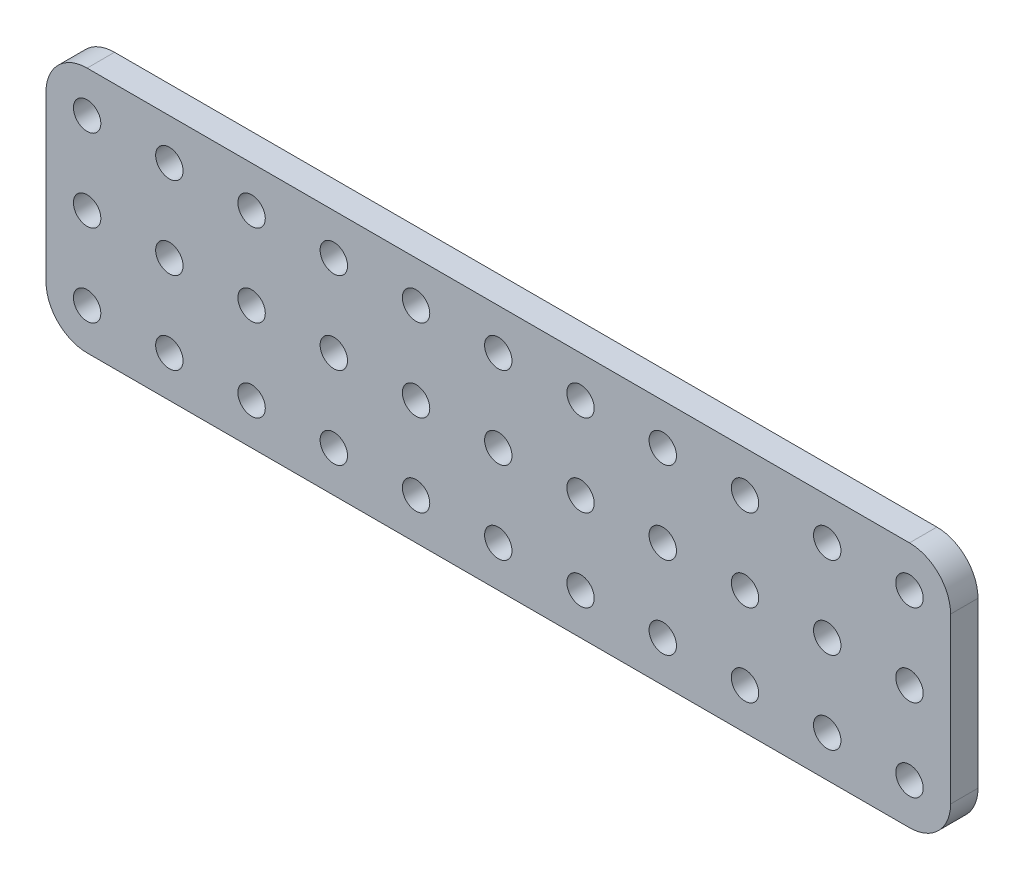
SolidWorks part; units mm, degrees
ref_plane "Alzado" through (0, 0, 0) normal (0, 0, 1) x (1, 0, 0)
ref_plane "Planta" through (0, 0, 0) normal (0, 1, 0) x (1, 0, 0)
ref_plane "Vista lateral" through (0, 0, 0) normal (1, 0, 0) x (0, 0, -1)
sketch "Model" plane through (0, 0, 0) normal (0, 0, 1) x (1, 0, 0)
  line L0 (256.4291, 237.7422) -> (346.4291, 237.7422)
  line L1 (346.4291, 210.7422) -> (256.4291, 210.7422)
  line L2 (350.9291, 233.2422) -> (350.9291, 215.2422)
  line L3 (251.9291, 233.2422) -> (251.9291, 215.2422)
  arc A0 (350.9291, 233.2422) -> (346.4291, 237.7422) centre (346.4291, 233.2422) ccw
  arc A1 (256.4291, 237.7422) -> (251.9291, 233.2422) centre (256.4291, 233.2422) ccw
  arc A2 (251.9291, 215.2422) -> (256.4291, 210.7422) centre (256.4291, 215.2422) ccw
  arc A3 (346.4291, 210.7422) -> (350.9291, 215.2422) centre (346.4291, 215.2422) ccw
  circle A4 centre (310.4291, 233.2422) radius 1.5
  circle A5 centre (292.4291, 233.2422) radius 1.5
  circle A6 centre (301.4291, 233.2422) radius 1.5
  circle A7 centre (337.4291, 215.2422) radius 1.5
  circle A8 centre (319.4291, 215.2422) radius 1.5
  circle A9 centre (328.4291, 215.2422) radius 1.5
  circle A10 centre (310.4291, 215.2422) radius 1.5
  circle A11 centre (292.4291, 215.2422) radius 1.5
  circle A12 centre (301.4291, 215.2422) radius 1.5
  circle A13 centre (274.4291, 215.2422) radius 1.5
  circle A14 centre (283.4291, 215.2422) radius 1.5
  circle A15 centre (265.4291, 215.2422) radius 1.5
  circle A16 centre (256.4291, 215.2422) radius 1.5
  circle A17 centre (346.4291, 215.2422) radius 1.5
  circle A18 centre (274.4291, 233.2422) radius 1.5
  circle A19 centre (265.4291, 233.2422) radius 1.5
  circle A20 centre (256.4291, 233.2422) radius 1.5
  circle A21 centre (283.4291, 233.2422) radius 1.5
  circle A22 centre (337.4291, 233.2422) radius 1.5
  circle A23 centre (319.4291, 233.2422) radius 1.5
  circle A24 centre (328.4291, 233.2422) radius 1.5
  circle A25 centre (346.4291, 233.2422) radius 1.5
  circle A26 centre (337.4291, 224.2422) radius 1.5
  circle A27 centre (319.4291, 224.2422) radius 1.5
  circle A28 centre (328.4291, 224.2422) radius 1.5
  circle A29 centre (310.4291, 224.2422) radius 1.5
  circle A30 centre (292.4291, 224.2422) radius 1.5
  circle A31 centre (301.4291, 224.2422) radius 1.5
  circle A32 centre (274.4291, 224.2422) radius 1.5
  circle A33 centre (283.4291, 224.2422) radius 1.5
  circle A34 centre (265.4291, 224.2422) radius 1.5
  circle A35 centre (256.4291, 224.2422) radius 1.5
  circle A36 centre (346.4291, 224.2422) radius 1.5
extrude "Saliente-Extruir1" add sketch "Model" along normal blind 3
